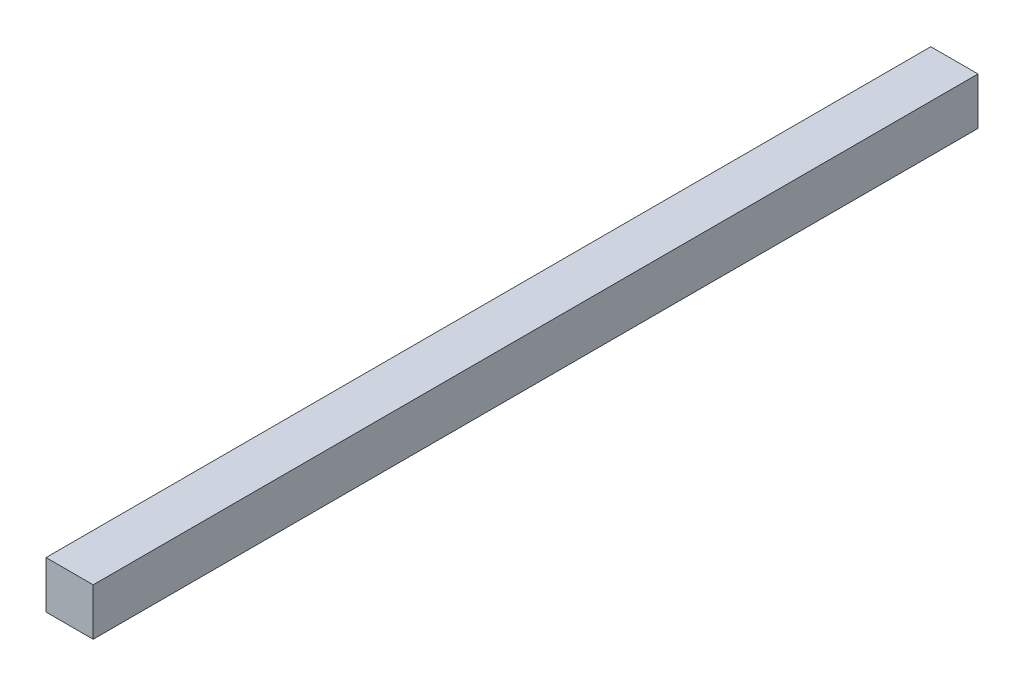
SolidWorks part; units mm, degrees
ref_plane "Front" through (0, 0, 0) normal (0, 0, 1) x (1, 0, 0)
ref_plane "Top" through (0, 0, 0) normal (0, 1, 0) x (1, 0, 0)
ref_plane "Right" through (0, 0, 0) normal (1, 0, 0) x (0, 0, -1)
sketch "Esquisse1" plane through (0, 0, 0) normal (0, 0, 1) x (1, 0, 0)
  line L1 (0, 0) -> (16, 0)
  line L2 (0, 0) -> (0, 16)
  line L3 (0, 16) -> (16, 16)
  line L4 (16, 0) -> (16, 16)
  dimension "D1" = 16
  dimension "D2" = 16
extrude "Boss.-Extru.1" add sketch "Esquisse1" along normal blind 300
